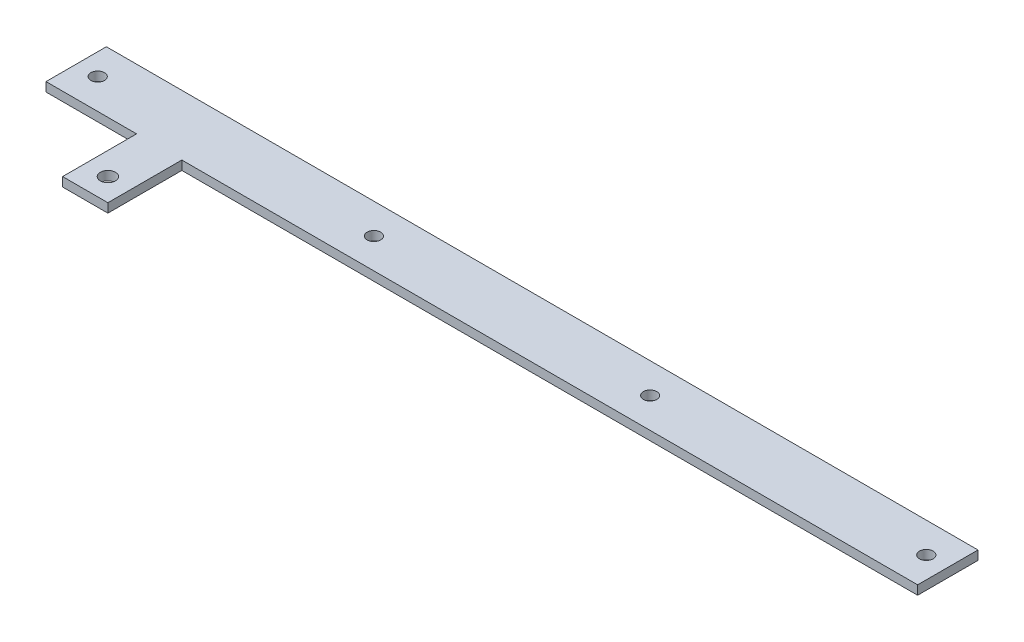
SolidWorks part; units mm, degrees
material "ASTM A36 Steel"
ref_plane "Front Plane" through (0, 0, 0) normal (0, 0, 1) x (1, 0, 0)
ref_plane "Top Plane" through (0, 0, 0) normal (0, 1, 0) x (1, 0, 0)
ref_plane "Right Plane" through (0, 0, 0) normal (1, 0, 0) x (0, 0, -1)
sketch "Sketch1" plane through (0, 0, 0) normal (0, 1, 0) x (1, 0, 0)
  line L1 (-577.5, -40) -> (577.5, -40)
  line L2 (-577.5, -40) -> (-577.5, 40)
  line L3 (-577.5, 40) -> (577.5, 40)
  line L4 (577.5, -40) -> (577.5, 40)
  line L5 (-577.5, -40) -> (577.5, 40) construction
  line L6 (-577.5, 40) -> (577.5, -40) construction
  point P0 (0, 0)
  dimension "D1" = 80
  dimension "D2" = 1155
extrude "Boss-Extrude1" add sketch "Sketch1" along normal blind 12
sketch "Sketch2" plane through (0, 12, 0) normal (0, 1, 0) x (1, 0, 0)
  line L0 (-577.5, 40) -> (-577.5, -40) construction
  circle A0 centre (-549, 0) radius 9
  dimension "D1" = 18
  dimension "D2" = 28.5
extrude "Cut-Extrude1" cut sketch "Sketch2" against normal through all both and the other way through all
pattern_linear "LPattern1" count 4 spacing 366 along (1, 0, 0) of "Cut-Extrude1"
sketch "Sketch3" plane through (0, 12, 0) normal (0, 1, 0) x (1, 0, 0)
  line L0 (-577.5, -40) -> (577.5, -40) construction
  line L1 (-457.5, -40) -> (-397.5, -40)
  line L2 (-457.5, -40) -> (-457.5, -138)
  line L3 (-457.5, -138) -> (-397.5, -138)
  line L4 (-397.5, -40) -> (-397.5, -138)
  line L5 (-577.5, 40) -> (-577.5, -40) construction
  circle A0 centre (-427.5, -108) radius 10
  dimension "D3" = 20
  dimension "D4" = 30
  dimension "D1" = 60
  dimension "D2" = 98
  dimension "D5" = 120
extrude "Boss-Extrude2" add sketch "Sketch3" against normal blind 12
